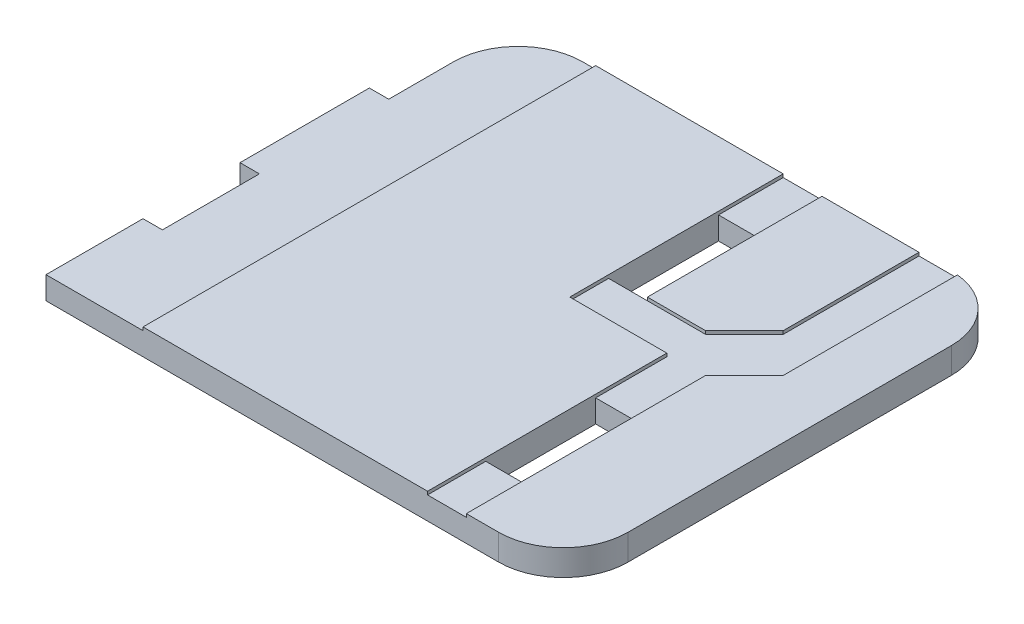
SolidWorks part; units mm, degrees
material "PBT General Purpose"
ref_plane "Front Plane" through (0, 0, 0) normal (0, 0, 1) x (1, 0, 0)
ref_plane "Top Plane" through (0, 0, 0) normal (0, 1, 0) x (1, 0, 0)
ref_plane "Right Plane" through (0, 0, 0) normal (1, 0, 0) x (0, 0, -1)
sketch "Sketch1" plane through (0, 0, 0) normal (0, 1, 0) x (1, 0, 0)
  line L0 (0, 0) -> (8, 0)
  line L5 (8, 0) -> (8, 7)
  line L6 (8, 7) -> (0.3, 7)
  line L7 (0.3, 7) -> (0.3, 5)
  line L8 (0.3, 5) -> (0, 5)
  line L9 (0, 5) -> (0, 3)
  line L10 (0, 3) -> (0.3, 3)
  line L11 (0.3, 3) -> (0.3, 1.5)
  line L12 (0.3, 1.5) -> (0, 1.5)
  line L13 (0, 1.5) -> (0, 0)
  line L15 (4.4, 6) -> (5, 6)
  line L16 (4.4, 6) -> (4.4, 4.3)
  line L17 (4.4, 4.3) -> (5, 4.3)
  line L18 (5, 6) -> (5, 4.3)
  line L19 (5.9, 0.9) -> (6.5, 0.9)
  line L20 (5.9, 0.9) -> (5.9, 2.6)
  line L21 (5.9, 2.6) -> (6.5, 2.6)
  line L22 (6.5, 0.9) -> (6.5, 2.6)
  dimension "D1" = 2
  dimension "D2" = 1.5
  dimension "D3" = 1.5
  dimension "D4" = 2
  dimension "D5" = 5.6
  dimension "D7" = 1.7
  dimension "D8" = 0.6
  dimension "D9" = 0.3
  dimension "D10" = 4.1
  dimension "D11" = 0.6
  dimension "D12" = 1.7
  dimension "D13" = 1
  dimension "D14" = 8
  dimension "D6" = 4.4
extrude "Boss-Extrude1" add sketch "Sketch1" along normal blind 0.4
fillet "Fillet1" radius 1 3 edges at (8, 0.2, 0) (8, 0.2, -7) (0.3, 0.2, -7)
sketch "Sketch3" plane through (0, 0.4, 0) normal (0, 1, 0) x (1, 0, 0)
  line L0 (7, 7) -> (1.3, 7) construction
  line L1 (4.4, 6) -> (5, 6)
  line L2 (4.4, 6) -> (4.4, 7)
  line L3 (4.4, 7) -> (5, 7)
  line L4 (5, 6) -> (5, 7)
  line L5 (0, 0) -> (7, 0) construction
  line L6 (5.9, 0.9) -> (6.5, 0.9)
  line L7 (5.9, 0.9) -> (5.9, 0)
  line L8 (5.9, 0) -> (6.5, 0)
  line L9 (6.5, 0.9) -> (6.5, 0)
  line L10 (6.5, 0.9) -> (6.5, 2.6) construction
  line L11 (5, 4.3) -> (5, 6) construction
  line L12 (4.4, 4.3) -> (4.4, 3.7)
  line L14 (6.5, 2.6) -> (5.9, 2.6)
  line L15 (4.4, 4.3) -> (5, 4.3)
  line L16 (5.9, 3.7) -> (5.9, 2.6)
  line L17 (6.5, 2.6) -> (6.5, 3.7)
  line L18 (0, 0) -> (1.5, 0)
  line L19 (0, 0) -> (0, 7)
  line L20 (0, 7) -> (1.5, 7)
  line L21 (1.5, 0) -> (1.5, 7)
  line L22 (4.4, 3.7) -> (5.9, 3.7)
  line L24 (5, 4.3) -> (5.9, 4.3)
  line L25 (5.9, 4.3) -> (6.5, 4.9)
  line L26 (6.5, 4.9) -> (6.5, 7)
  line L27 (6.5, 3.7) -> (7.1, 4.3)
  line L28 (7.1, 4.3) -> (7.1, 6.995)
  line L29 (7.1, 6.995) -> (7.1, 7.2689)
  line L30 (7.1, 7.2689) -> (6.5, 7.2689)
  line L31 (6.5, 7.2689) -> (6.5, 7)
  arc A0 (8, 6) -> (7, 7) centre (7, 6) ccw construction
  line M15 (0, 0) -> (7, 0)
  line M19 (7, 7) -> (1.3, 7)
  arc M20 (1.3, 7) -> (0.3, 6) centre (1.3, 6) ccw
  line M21 (0.3, 6) -> (0.3, 5)
  line M22 (0.3, 5) -> (0, 5)
  line M23 (0, 5) -> (0, 3)
  line M24 (0, 3) -> (0.3, 3)
  line M25 (0.3, 3) -> (0.3, 1.5)
  line M26 (0.3, 1.5) -> (0, 1.5)
  line M27 (0, 1.5) -> (0, 0)
  dimension "D1" = 1.5
extrude "Cut-Extrude2" cut sketch "Sketch3" against normal blind 0.05 contours L21 M15 M19 M20 M21 M22 M23 M24 M25 M26 M27 | L7 L6 L9 L8 | L15 L24 L25 L26 L31 L30 L29 L28 L27 L17 L14 L16 L22 L12 | L2 L1 L4 L3
equation "\"t\"= 0.3'thickness of the sheets"
equation "\"FlexJoint\"= 0.15'Width of flextures"
equation "\"FoldJoint\"= 0.4'Width of folding joints"
equation "\"AssembleAngle\"= 90'Angle of assembly parts"
equation "\"D9@Sketch1\"=\"t\""
